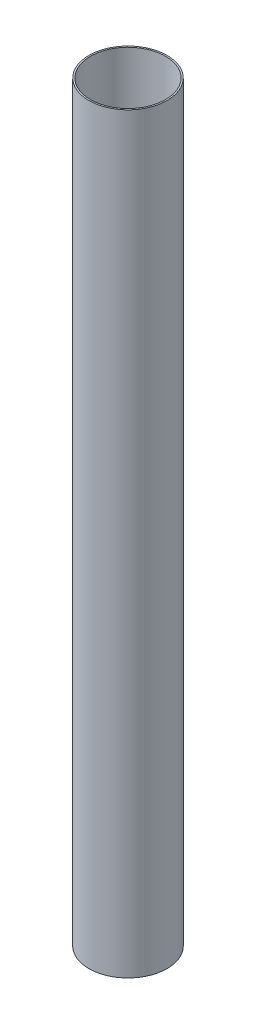
SolidWorks part; units mm, degrees
material "S-Glass Fiber"
ref_plane "Front Plane" through (0, 0, 0) normal (0, 0, 1) x (1, 0, 0)
ref_plane "Top Plane" through (0, 0, 0) normal (0, 1, 0) x (1, 0, 0)
ref_plane "Right Plane" through (0, 0, 0) normal (1, 0, 0) x (0, 0, -1)
sketch "Sketch1" plane through (0, 0, 0) normal (0, 1, 0) x (1, 0, 0)
  circle A0 centre (0, 0) radius 39.624
  circle A1 centre (0, 0) radius 38.1
  dimension "D1" = 79.248
  dimension "D2" = 76.2
extrude "Boss-Extrude1" add sketch "Sketch1" along normal blind 762
